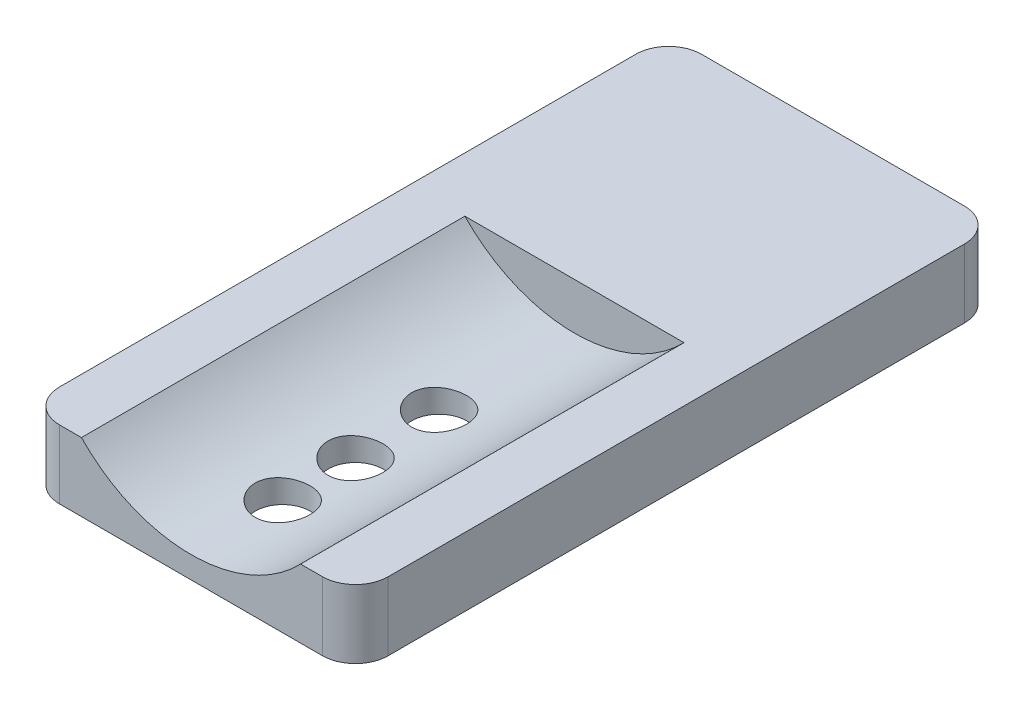
SolidWorks part; units mm, degrees
ref_plane "Front Plane" through (0, 0, 0) normal (0, 0, 1) x (1, 0, 0)
ref_plane "Top Plane" through (0, 0, 0) normal (0, 1, 0) x (1, 0, 0)
ref_plane "Right Plane" through (0, 0, 0) normal (1, 0, 0) x (0, 0, -1)
sketch "Sketch1" plane through (0, 0, 0) normal (1, 0, 0) x (0, 0, -1)
  line L0 (0, 0) -> (58.6, 0)
  line L1 (58.6, 0) -> (58.6, 6.25)
  line L2 (58.6, 6.25) -> (0, 6.25)
  line L3 (0, 6.25) -> (0, 0)
  line L4 (0, 3.125) -> (58.6, 3.125) construction
  dimension "D1" = 58.6
  dimension "D2" = 6.25
extrude "Boss-Extrude1" add sketch "Sketch1" along normal blind 30
sketch "Sketch2" plane through (0, 0, 0) normal (0, 0, 1) x (1, 0, 0)
  line L0 (30, 6.25) -> (0, 6.25) construction
  line L1 (5, 6.25) -> (25, 6.25)
  line L2 (5, 6.25) -> (25, 6.25)
  arc A0 (5, 6.25) -> (25, 6.25) centre (15, 15.8897) ccw
  point P3 (15, 2)
  dimension "D1" = 5
  dimension "D2" = 5
  dimension "D3" = 4.25
extrude "Cut-Extrude1" cut sketch "Sketch2" against normal blind 35 and the other way through all contours A0
sketch "Sketch4" plane through (0, 0, 0) normal (0, -1, 0) x (1, 0, 0)
  line L1 (22.8, -38.1) -> (22.8, -5)
  line L2 (22.8, -5) -> (7.2, -5)
  line L3 (7.2, -5) -> (7.2, -38.1)
  line L4 (30, -58.6) -> (0, -58.6) construction
  line L5 (22.8, -38.1) -> (22.8, -48.6)
  line L6 (7.2, -38.1) -> (22.8, -38.1)
  line L10 (22.8, -48.6) -> (7.2, -48.6)
  line L11 (7.2, -48.6) -> (7.2, -38.1)
  line L13 (30, 0) -> (0, 0) construction
  circle A0 centre (15, -8.37) radius 2.5
  circle A1 centre (15, -15.02) radius 2.5
  circle A2 centre (15, -22.65) radius 2.5
  point P7 (15, -58.6)
  point P12 (15, -5)
  point P20 (15, 0)
  dimension "D4" = 5
  dimension "D8" = 5
  dimension "D9" = 5
  dimension "D2" = 10.5
  dimension "D3" = 43.6
  dimension "D5" = 5
  dimension "D7" = 15.6
  dimension "D10" = 3.37
  dimension "D11" = 10.02
  dimension "D12" = 17.65
extrude "Cut-Extrude2" cut sketch "Sketch4" against normal blind 4
sketch "Sketch5" plane through (0, 0, -58.6) normal (0, 0, -1) x (-1, 0, 0)
  line L9 (-30, 0) -> (0, 0) construction
  line L11 (-30, 6.25) -> (0, 6.25) construction
  line L13 (-9.85, 1) -> (-20.15, 1)
  line L15 (-20.15, 5.25) -> (-9.85, 5.25)
  line L18 (-9.85, 5.25) -> (-9.85, 1)
  line L19 (-20.15, 1) -> (-18.025, 3.125)
  line L20 (-18.025, 3.125) -> (-20.15, 5.25)
  point P5 (-15, 1)
  point P10 (-15, 0)
  point P12 (-9.85, 3.125)
  dimension "D1" = 10.3
  dimension "D2" = 1
  dimension "D3" = 1
extrude "Cut-Extrude3" cut sketch "Sketch5" against normal blind 9.5
sketch "Sketch6" plane through (0, 0, 0) normal (0, -1, 0) x (1, 0, 0)
  line L1 (7.2, -38.1) -> (22.8, -38.1)
  line L2 (7.2, -38.1) -> (7.2, -37.1)
  line L3 (7.2, -37.1) -> (22.8, -37.1)
  line L4 (22.8, -38.1) -> (22.8, -37.1)
  line L5 (22.8, -48.6) -> (7.2, -48.6)
  line L6 (22.8, -48.6) -> (22.8, -49.1)
  line L7 (22.8, -49.1) -> (7.2, -49.1)
  line L8 (7.2, -48.6) -> (7.2, -49.1)
  dimension "D1" = 0.5
  dimension "D2" = 1
extrude "Cut-Extrude4" cut sketch "Sketch6" against normal up to surface (4 mm away) up to face at (15, 4, -43.35)
fillet "Fillet1" radius 3 4 edges at (0, 3.125, 0) (0, 3.125, -58.6) (30, 3.125, -58.6) (30, 3.125, 0)
sketch "Sketch7" plane through (0, 0, 0) normal (0, -1, 0) x (1, 0, 0)
  line L0 (0, -3) -> (0, -55.6) construction
  line L1 (27, -58.6) -> (3, -58.6) construction
  line L2 (15, -58.6) -> (15, 0) construction
  line L3 (27, 0) -> (3, 0) construction
  line L4 (30, -29.3) -> (0, -29.3) construction
  line L5 (30, -3) -> (30, -55.6) construction
  circle A0 centre (3, -55.6) radius 1.65
  circle A1 centre (27, -55.6) radius 1.65
  circle A2 centre (27, -3) radius 1.65
  circle A3 centre (3, -3) radius 1.65
  dimension "D1" = 3.3
  dimension "D2" = 3
  dimension "D3" = 3
extrude "Cut-Extrude5" cut sketch "Sketch7" against normal blind 3
